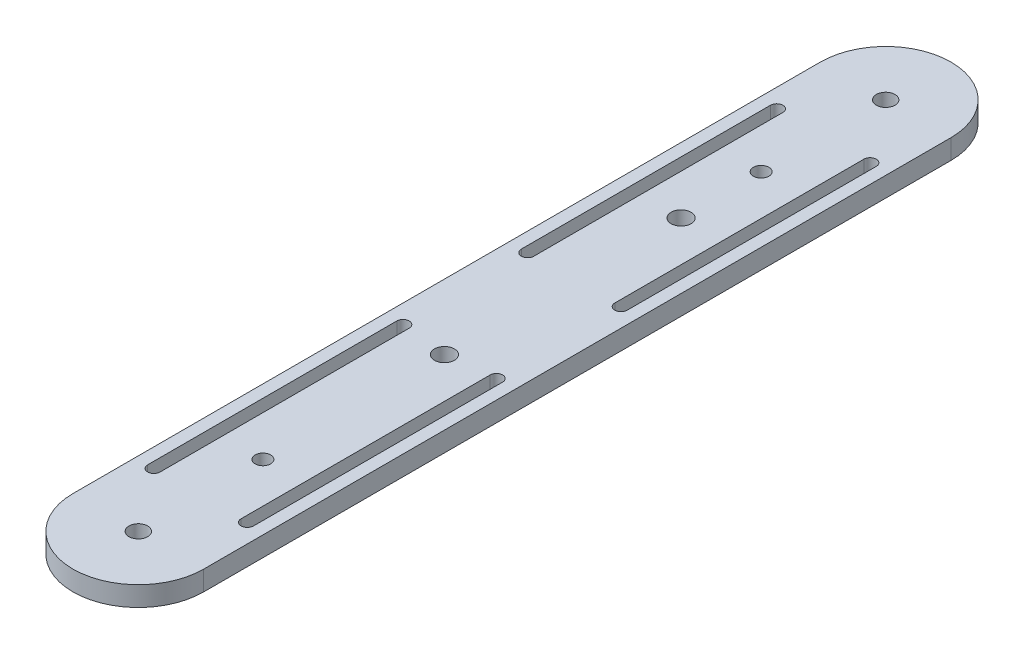
SolidWorks part; units mm, degrees
ref_plane "Front Plane" through (0, 0, 0) normal (0, 0, 1) x (1, 0, 0)
ref_plane "Top Plane" through (0, 0, 0) normal (0, 1, 0) x (1, 0, 0)
ref_plane "Right Plane" through (0, 0, 0) normal (1, 0, 0) x (0, 0, -1)
sketch "Sketch1" plane through (0, 0, 0) normal (0, 1, 0) x (1, 0, 0)
  line L0 (-10.5, 0) -> (-10.5, -120)
  line L1 (10.5, 0) -> (10.5, -120)
  arc A0 (10.5, 0) -> (-10.5, 0) centre (0, 0) ccw
  arc A1 (-10.5, -120) -> (10.5, -120) centre (0, -120) ccw
  circle A2 centre (0, 0) radius 1.5
  circle A5 centre (0, -120) radius 1.5
  dimension "D1" = 10.5
  dimension "D3" = 3
  dimension "D2" = 120
extrude "Boss-Extrude1" add sketch "Sketch1" along normal blind 3.175
sketch "Sketch2" plane through (0, 0, 0) normal (0, -1, 0) x (1, 0, 0)
  arc A0 (0, 18.75) -> (0, 21.25) centre (0, 20) ccw construction
  arc A1 (0, 21.25) -> (0, 18.75) centre (0, 20) ccw construction
  arc A4 (0, 18.75) -> (0, 21.25) centre (0, 20) ccw
  arc A5 (0, 21.25) -> (0, 18.75) centre (0, 20) ccw
extrude "Cut-Extrude1" cut sketch "Sketch2" against normal through all both and the other way through all
sketch "Sketch3" plane through (0, 3.175, 0) normal (0, 1, 0) x (1, 0, 0)
  arc A2 (0, -98.75) -> (0, -101.25) centre (0, -100) ccw construction
  arc A3 (0, -101.25) -> (0, -98.75) centre (0, -100) ccw construction
  arc A6 (0, -98.75) -> (0, -101.25) centre (0, -100) ccw
  arc A7 (0, -101.25) -> (0, -98.75) centre (0, -100) ccw
extrude "Cut-Extrude2" cut sketch "Sketch3" against normal through all both and the other way through all
sketch "Sketch5" plane through (0, 0, 0) normal (0, -1, 0) x (1, 0, 0)
  line L0 (0, -10.5) -> (0, 130.5) construction
  line L1 (-10.5, 60) -> (10.5, 60) construction
  line L2 (-10.5, 0) -> (-10.5, 120) construction
  line L3 (10.5, 120) -> (10.5, 0) construction
  line L6 (-8.5, 10) -> (-8.5, 50)
  line L7 (-6.5, 50) -> (-6.5, 10)
  line L8 (6.5, 50) -> (6.5, 10)
  line L9 (8.5, 10) -> (8.5, 50)
  line L22 (8.5, 110) -> (8.5, 70)
  line L23 (6.5, 70) -> (6.5, 110)
  line L24 (-6.5, 70) -> (-6.5, 110)
  line L25 (-8.5, 110) -> (-8.5, 70)
  arc A0 (-10.5, 0) -> (10.5, 0) centre (0, 0) ccw construction
  arc A1 (10.5, 120) -> (-10.5, 120) centre (0, 120) ccw construction
  arc A4 (-8.5, 10) -> (-6.5, 10) centre (-7.5, 10) ccw
  arc A5 (-6.5, 50) -> (-8.5, 50) centre (-7.5, 50) ccw
  arc A6 (6.5, 50) -> (8.5, 50) centre (7.5, 50) cw
  arc A7 (8.5, 10) -> (6.5, 10) centre (7.5, 10) cw
  arc A20 (8.5, 110) -> (6.5, 110) centre (7.5, 110) ccw
  arc A21 (6.5, 70) -> (8.5, 70) centre (7.5, 70) ccw
  arc A22 (-6.5, 70) -> (-8.5, 70) centre (-7.5, 70) cw
  arc A23 (-8.5, 110) -> (-6.5, 110) centre (-7.5, 110) cw
  dimension "D1" = 40
  dimension "D3" = 10
  dimension "D2" = 2
  dimension "D4" = 3
extrude "Cut-Extrude4" cut sketch "Sketch5" against normal blind 40
sketch "Sketch6" plane through (0, 0, 0) normal (0, -1, 0) x (1, 0, 0)
  circle A0 centre (0, 70.85) radius 1.6 construction
  circle A1 centre (0, 32.85) radius 1.6 construction
  circle A2 centre (0, 70.85) radius 1.6
  circle A3 centre (0, 32.85) radius 1.6
extrude "Cut-Extrude5" cut sketch "Sketch6" against normal blind 10
